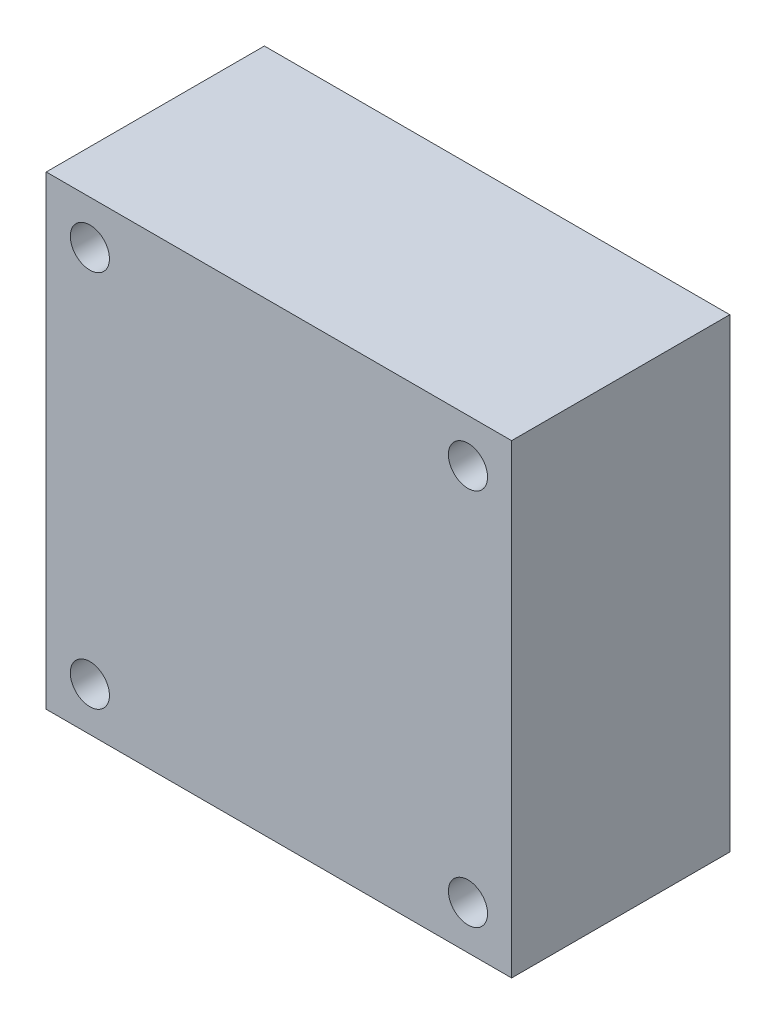
SolidWorks part; units mm, degrees
ref_plane "Front Plane" through (0, 0, 0) normal (0, 0, 1) x (1, 0, 0)
ref_plane "Top Plane" through (0, 0, 0) normal (0, 1, 0) x (1, 0, 0)
ref_plane "Right Plane" through (0, 0, 0) normal (1, 0, 0) x (0, 0, -1)
sketch "Sketch1" plane through (0, 0, 0) normal (0, 0, 1) x (1, 0, 0)
  line L0 (0, 16) -> (0, -16) construction
  line L1 (16, -16) -> (-16, -16)
  line L2 (16, -16) -> (16, 16)
  line L3 (16, 16) -> (-16, 16)
  line L4 (-16, -16) -> (-16, 16)
  line L5 (16, -16) -> (-16, 16) construction
  line L6 (16, 16) -> (-16, -16) construction
  line L7 (-16, -13) -> (16, -13) construction
  line L8 (-16, 0) -> (16, 0) construction
  line L9 (-16, 13) -> (16, 13) construction
  circle A0 centre (-13, -13) radius 1.3455
  circle A1 centre (13, -13) radius 1.3455
  circle A2 centre (13, 13) radius 1.3455
  circle A3 centre (-13, 13) radius 1.3455
  point P0 (0, 0)
  dimension "D1" = 32
  dimension "D2" = 32
  dimension "D3" = 26
  dimension "D4" = 26
extrude "Boss-Extrude1" add sketch "Sketch1" along normal blind 15
